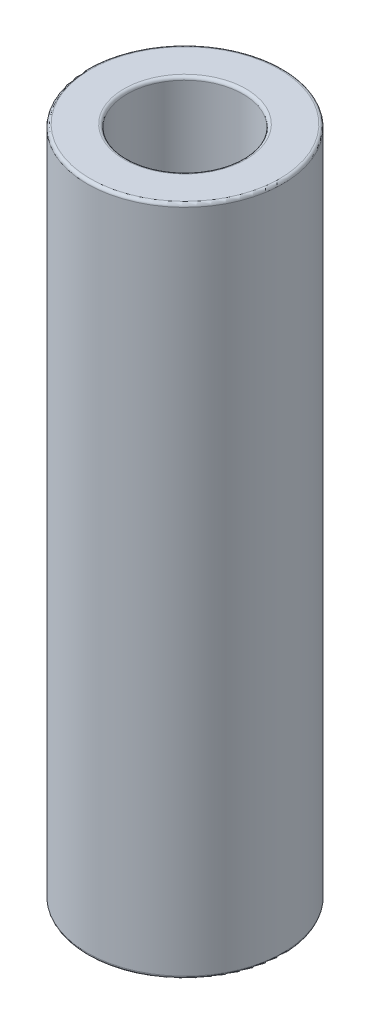
SolidWorks part; units mm, degrees
ref_plane "Front Plane" through (0, 0, 0) normal (0, 0, 1) x (1, 0, 0)
ref_plane "Top Plane" through (0, 0, 0) normal (0, 1, 0) x (1, 0, 0)
ref_plane "Right Plane" through (0, 0, 0) normal (1, 0, 0) x (0, 0, -1)
sketch "Sketch1" plane through (0, 0, 0) normal (0, 1, 0) x (1, 0, 0)
  circle A0 centre (0, 0) radius 9.5
  circle A1 centre (0, 0) radius 16
  dimension "D1" = 19
  dimension "D2" = 32
extrude "Boss-Extrude1" add sketch "Sketch1" along normal blind 110 contours A1 A0
fillet "Fillet1" radius 0.5 4 edges at (0, 110, 16) (0, 110, 9.5) (0, 0, 16) (0, 0, 9.5)
